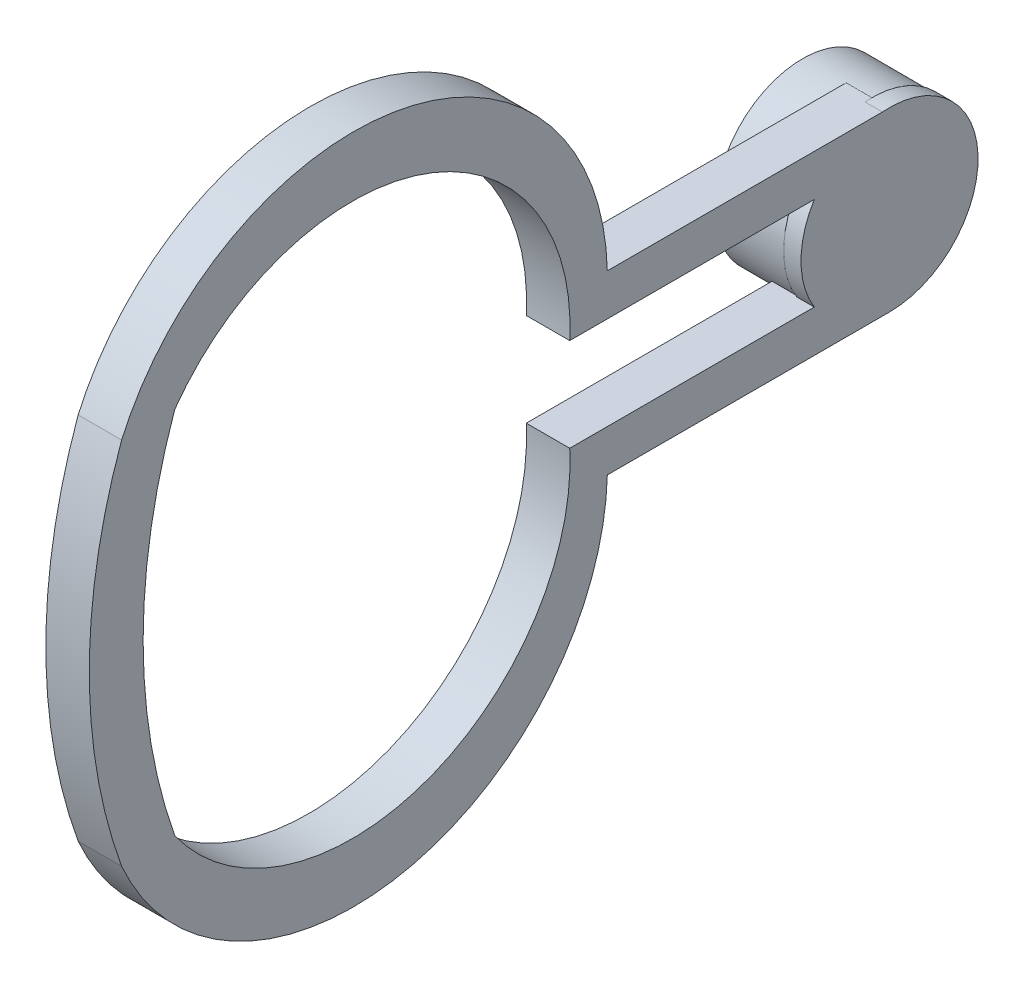
SolidWorks part; units mm, degrees
ref_plane "Front Plane" through (0, 0, 0) normal (0, 0, 1) x (1, 0, 0)
ref_plane "Top Plane" through (0, 0, 0) normal (0, 1, 0) x (1, 0, 0)
ref_plane "Right Plane" through (0, 0, 0) normal (1, 0, 0) x (0, 0, -1)
sketch "Sketch5" plane through (0, 0, 0) normal (1, 0, 0) x (0, 0, -1)
  circle A74 centre (0.3347, 2.225) radius 0.127
  circle A75 centre (0.7266, 2.1295) radius 0.127
  circle A76 centre (1.0952, 1.9655) radius 0.127
  circle A77 centre (1.4285, 1.7384) radius 0.127
  circle A78 centre (1.7159, 1.4554) radius 0.127
  circle A79 centre (1.9482, 1.1256) radius 0.127
  circle A80 centre (2.1179, 0.7596) radius 0.127
  circle A81 centre (2.2195, 0.3692) radius 0.127
  circle A82 centre (2.2498, -0.033) radius 0.127
  circle A83 centre (2.2077, -0.4342) radius 0.127
  circle A84 centre (2.0947, -0.8214) radius 0.127
  circle A85 centre (1.9144, -1.1822) radius 0.127
  circle A86 centre (1.6725, -1.5051) radius 0.127
  circle A87 centre (1.3769, -1.7795) radius 0.127
  circle A88 centre (1.037, -1.9968) radius 0.127
  circle A89 centre (0.6638, -2.1498) radius 0.127
  circle A90 centre (0.2693, -2.2338) radius 0.127
  circle A91 centre (-0.1339, -2.246) radius 0.127
  circle A92 centre (-0.5328, -2.186) radius 0.127
  circle A93 centre (-0.9146, -2.0557) radius 0.127
  circle A94 centre (-1.2669, -1.8594) radius 0.127
  circle A95 centre (-1.5786, -1.6033) radius 0.127
  circle A96 centre (-1.8395, -1.2957) radius 0.127
  circle A97 centre (-2.0413, -0.9464) radius 0.127
  circle A98 centre (-2.1775, -0.5667) radius 0.127
  circle A99 centre (-2.2437, -0.1688) radius 0.127
  circle A100 centre (-2.2377, 0.2345) radius 0.127
  circle A101 centre (-2.1599, 0.6303) radius 0.127
  circle A102 centre (-2.0126, 1.0059) radius 0.127
  circle A103 centre (-1.8007, 1.3491) radius 0.127
  circle A104 centre (-1.5309, 1.6489) radius 0.127
  circle A105 centre (-1.2118, 1.8958) radius 0.127
  circle A106 centre (-0.8539, 2.0817) radius 0.127
  circle A107 centre (-0.4684, 2.2007) radius 0.127
  circle A108 centre (-0.068, 2.249) radius 0.127
  point P75 (0, 0)
extrude "Boss-Extrude6" add sketch "Sketch5" along normal blind 1.524 and the other way blind 3.048
sketch "Sketch10" plane through (-3.048, 0, 0) normal (-1, 0, 0) x (0, 0, 1)
  circle A0 centre (0, 0) radius 0.7239
extrude "Boss-Extrude13" add sketch "Sketch10" against normal blind 4.572 separate body contours A0
sketch "Sketch8" plane through (1.016, 0, 0) normal (-1, 0, 0) x (0, 0, 1)
  line L9 (0, 2.7231) -> (0, 5.1566)
  line L10 (0, 5.1566) -> (16.4899, 5.1566)
  line L13 (0, 2.7231) -> (18.6868, 2.7231)
  line L16 (0, -2.7231) -> (18.6868, -2.7231)
  line L17 (0, -5.1731) -> (16.4903, -5.1731)
  line L18 (0, -2.7231) -> (0, -5.1731)
  arc A6 (16.4899, 5.1566) -> (44.8716, 10.7868) centre (31.3119, 4.7899) cw
  arc A10 (18.6868, 2.7231) -> (41.7663, 10.7868) centre (31.399, 3.3994) cw
  arc A11 (18.6868, -2.7231) -> (41.7663, -10.7868) centre (31.399, -3.3994) ccw
  arc A12 (16.4903, -5.1731) -> (44.8716, -10.7868) centre (31.3119, -4.7899) ccw
  arc A13 (41.7663, 10.7868) -> (41.7663, -10.7868) centre (11.2391, 0) cw
  arc A14 (44.8716, 10.7868) -> (44.8716, -10.7868) centre (15.0413, 0) cw
extrude "Boss-Extrude9" add sketch "Sketch8" along normal blind 1.524 and the other way blind 1.016
sketch "Sketch9" plane through (1.016, 0, 0) normal (-1, 0, 0) x (0, 0, 1)
  circle A0 centre (0, 0) radius 5.1731
extrude "Boss-Extrude10" add sketch "Sketch9" against normal blind 1.016
sketch "Sketch12" plane through (1.016, 0, 0) normal (-1, 0, 0) x (0, 0, 1)
  circle A0 centre (0, 0) radius 2.2424
  circle A1 centre (0, 0) radius 5.1113
extrude "Boss-Extrude15" add sketch "Sketch12" along normal blind 4.064
sketch "Sketch13" plane through (-3.048, 0, 0) normal (-1, 0, 0) x (0, 0, 1)
  circle A0 centre (0, 0) radius 3.6969
extrude "Cut-Extrude1" cut sketch "Sketch13" against normal blind 4.572
